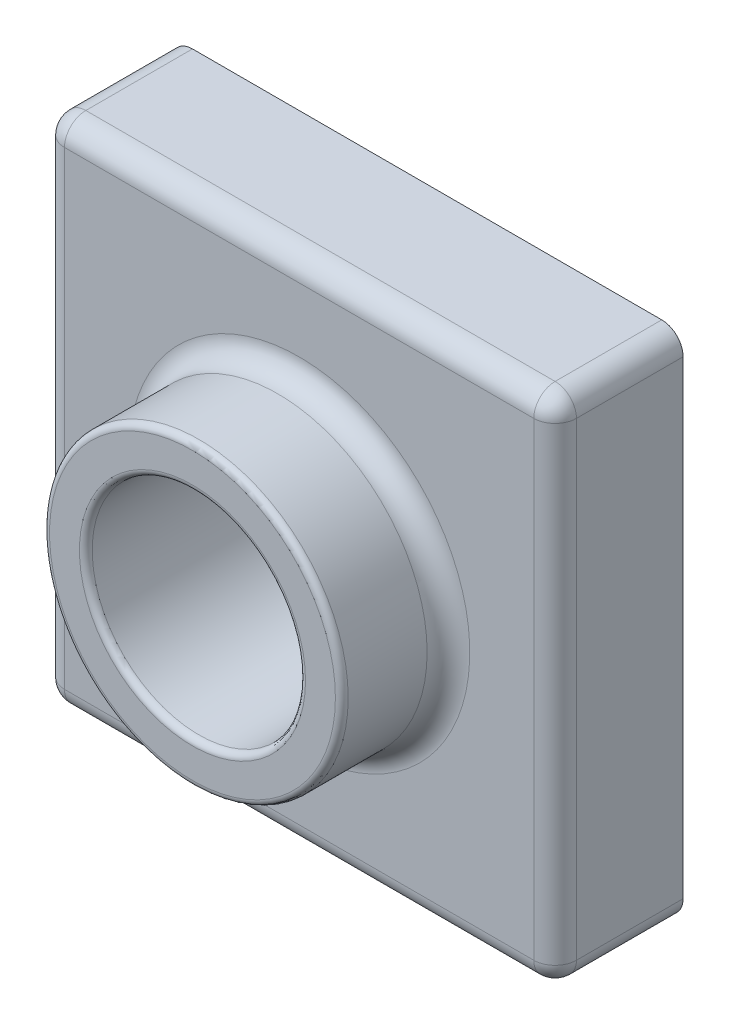
SolidWorks part; units mm, degrees
ref_plane "Front Plane" through (0, 0, 0) normal (0, 0, 1) x (1, 0, 0)
ref_plane "Top Plane" through (0, 0, 0) normal (0, 1, 0) x (1, 0, 0)
ref_plane "Right Plane" through (0, 0, 0) normal (1, 0, 0) x (0, 0, -1)
sketch "Sketch2" plane through (0, 0, 0) normal (0, 0, 1) x (1, 0, 0)
  line L1 (0, 0) -> (120, 0)
  line L2 (0, 0) -> (0, 120)
  line L3 (0, 120) -> (120, 120)
  line L4 (120, 0) -> (120, 120)
  dimension "D1" = 120
  dimension "D2" = 120
extrude "Boss-Extrude1" add sketch "Sketch2" along normal blind 30
sketch "Sketch3" plane through (0, 0, 30) normal (0, 0, 1) x (1, 0, 0)
  line L0 (120, 120) -> (0, 120) construction
  line L1 (120, 0) -> (120, 120) construction
  circle A0 centre (60, 60) radius 35
  dimension "D1" = 70
  dimension "D2" = 60
  dimension "D3" = 60
extrude "Boss-Extrude2" add sketch "Sketch3" along normal blind 25
sketch "Sketch4" plane through (0, 0, 55) normal (0, 0, 1) x (1, 0, 0)
  circle A0 centre (60, 60) radius 25
  dimension "D1" = 50
extrude "Cut-Extrude1" cut sketch "Sketch4" against normal through all
fillet "Fillet2" radius 5 9 edges at (25, 60, 30) (60, 120, 30) (120, 60, 30) (60, 0, 30) (0, 60, 30) (0, 0, 15) (120, 0, 15) (0, 120, 15) (120, 120, 15)
fillet "Fillet3" radius 1.5 2 edges at (95, 60, 55) (85, 60, 55)
shell "Shell1" thickness 2
